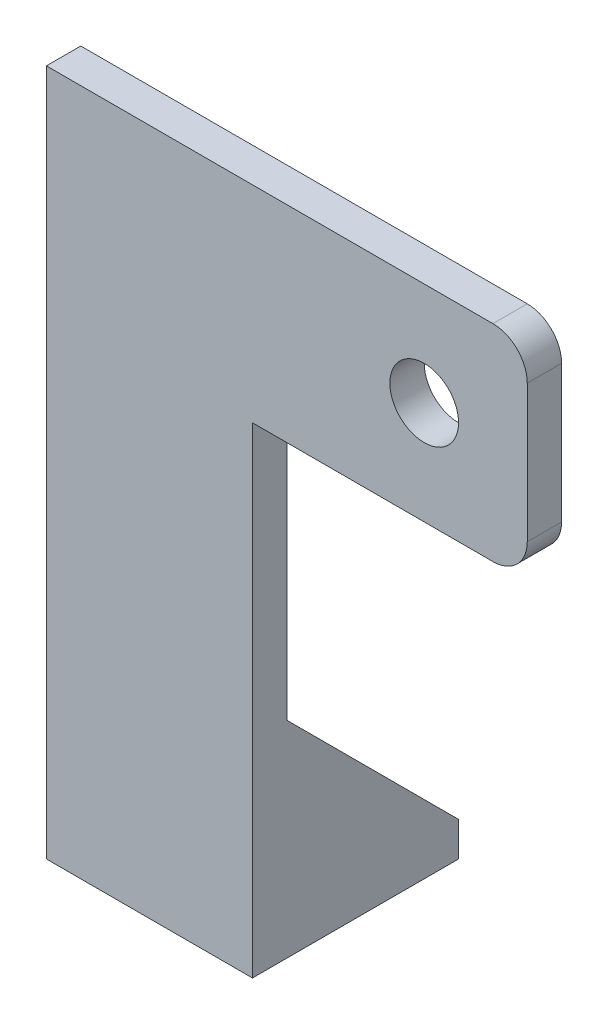
SolidWorks part; units mm, degrees
ref_plane "Front Plane" through (0, 0, 0) normal (0, 0, 1) x (1, 0, 0)
ref_plane "Top Plane" through (0, 0, 0) normal (0, 1, 0) x (1, 0, 0)
ref_plane "Right Plane" through (0, 0, 0) normal (1, 0, 0) x (0, 0, -1)
sketch "Sketch1" plane through (0, 0, 0) normal (0, 0, 1) x (1, 0, 0)
  line L0 (0, -15) -> (6.6093, -15) construction
  line L1 (5, 0) -> (70, 0)
  line L2 (0, -5) -> (0, -25)
  line L3 (5, -30) -> (40, -30)
  line L4 (70, 0) -> (70, -30)
  line L6 (70, -30) -> (70, -95)
  line L7 (70, -95) -> (40, -95)
  line L8 (40, -30) -> (40, -95)
  arc A1 (5, 0) -> (0, -5) centre (5, -5) ccw
  arc A2 (5, -30) -> (0, -25) centre (5, -25) cw
  dimension "D5" = 10
  dimension "D1" = 30
  dimension "D2" = 70
  dimension "D3" = 30
  dimension "D4" = 65
extrude "Boss-Extrude1" add sketch "Sketch1" along normal blind 5 contours L1 L4 L6 L7 L8 L3 A2 L2 A1
ref_plane "Plane1" through (55, 0, 0) normal (-1, 0, 0) x (0, 0, 1)
sketch "Sketch4" plane through (0, 0, 5) normal (0, 0, 1) x (1, 0, 0)
  line L0 (0, -5) -> (0, -25) construction
  line L1 (5, 0) -> (70, 0) construction
  circle A0 centre (15, -15) radius 5
  dimension "D1" = 10
  dimension "D2" = 15
  dimension "D3" = 15
extrude "Cut-Extrude1" cut sketch "Sketch4" against normal blind 5 contours A0
sketch "Sketch5" plane through (0, -95, 0) normal (0, -1, 0) x (1, 0, 0)
  line L0 (70, 5) -> (70, 0) construction
  line L1 (40, 5) -> (70, 5)
  line L2 (40, 5) -> (40, -25)
  line L3 (40, -25) -> (70, -25)
  line L4 (70, 5) -> (70, -25)
  dimension "D1" = 30
extrude "Boss-Extrude4" add sketch "Sketch5" along normal blind 5
sketch "Sketch6" plane through (70, 0, 0) normal (1, 0, 0) x (0, 0, -1)
  line L0 (0, -70) -> (25, -95)
  line L1 (0, 0) -> (0, -95) construction
  line L2 (0, -70) -> (0, -95)
  line L3 (0, -95) -> (25, -95)
extrude "Boss-Extrude5" add sketch "Sketch6" against normal blind 5
mirror "Mirror2" about plane through (55, 0, 0) normal (-1, 0, 0) of "Boss-Extrude5"
mirror "Mirror4" about plane through (55, 0, 0) normal (-1, 0, 0) of "Boss-Extrude1"
sketch "Sketch9" plane through (0, 0, 0) normal (0, 0, -1) x (-1, 0, 0)
  line L0 (-110, -5) -> (-110, -25) construction
  line L1 (-5, 0) -> (-105, 0) construction
  circle A0 centre (-95, -15) radius 5
  dimension "D1" = 10
  dimension "D2" = 15
  dimension "D3" = 15
extrude "Cut-Extrude4" cut sketch "Sketch9" against normal blind 10 contours A0
sketch "Sketch10" plane through (0, 0, 0) normal (0, 0, -1) x (-1, 0, 0)
  line L1 (-40, -30) -> (5.0273, -30)
  line L2 (-40, -30) -> (-40, 1.5058)
  line L3 (-40, 1.5058) -> (5.0273, 1.5058)
  line L4 (5.0273, -30) -> (5.0273, 1.5058)
extrude "Cut-Extrude5" cut sketch "Sketch10" against normal blind 10
